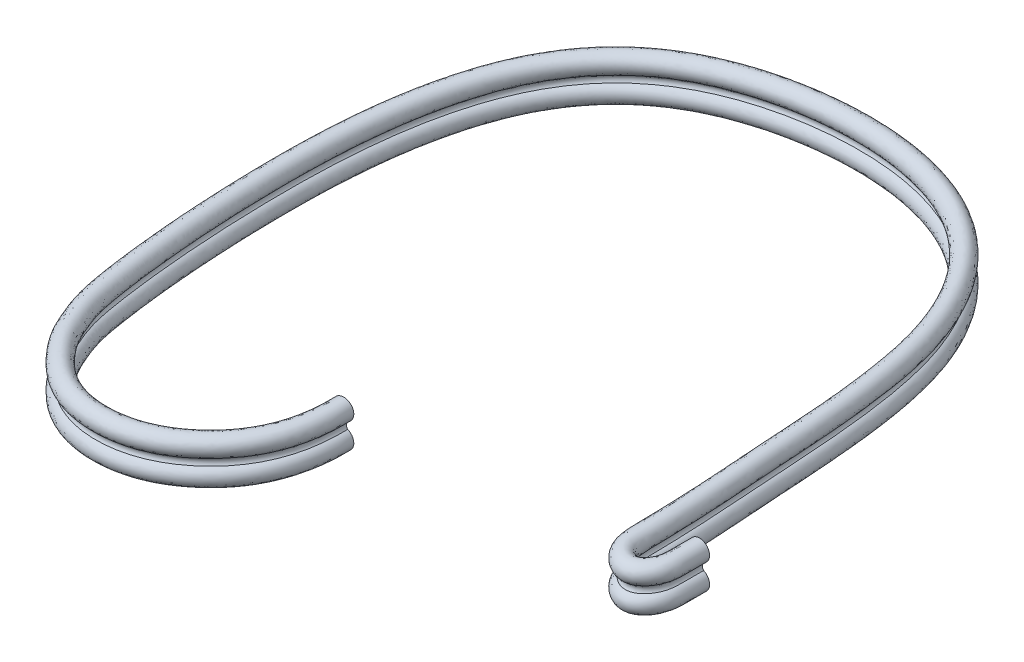
SolidWorks part; units mm, degrees
material "ABS"
ref_plane "Plan de face" through (0, 0, 0) normal (0, 0, 1) x (1, 0, 0)
ref_plane "Plan de dessus" through (0, 0, 0) normal (0, 1, 0) x (1, 0, 0)
ref_plane "Plan de droite" through (0, 0, 0) normal (1, 0, 0) x (0, 0, -1)
sketch "Esquisse1" plane through (0, 0, 0) normal (0, 0, 1) x (1, 0, 0)
  arc A0 (-18.3775, -10.301) -> (-18.0489, -10.301) centre (-18.2132, -10.6657) ccw construction
  arc A1 (-18.3775, -10.301) -> (-18.0489, -10.301) centre (-18.2132, -10.6657) ccw
  arc A2 (-18.0489, -10.0304) -> (-18.0489, -10.301) centre (-17.8955, -10.1657) ccw
  arc A3 (-18.3775, -10.301) -> (-18.3775, -10.0304) centre (-18.5309, -10.1657) ccw construction
  arc A4 (-18.3775, -10.301) -> (-18.3775, -10.0304) centre (-18.5309, -10.1657) ccw
  arc A5 (-18.0489, -10.0304) -> (-18.3775, -10.0304) centre (-18.2132, -9.6657) ccw construction
  arc A6 (-18.0489, -10.0304) -> (-18.3775, -10.0304) centre (-18.2132, -9.6657) ccw
sketch "Esquisse2" plane through (0, -10.1657, 0) normal (0, 1, 0) x (-1, 0, 0)
  line L0 (18.6132, 0) -> (17.8132, 0) construction
  spline S0 degree 3 poles (18.2132, 0) (18.2131, 0.269) (18.213, 0.7207) (18.2139, 1.4918) (18.8445, 2.3266) (19.7802, 1.6372) (19.8062, -1.3841) (20.063, -4.1507) (20.4795, -12.6435) (25.2659, -18.3191) (35.6574, -17.5688) (39.4688, -11.5212) (39.6429, -2.674) (39.0035, 3.1107) (38.6649, 4.1118) (37.8731, 5.8569) (35.689, 7.7295) (31.9405, 7.169) (30.0632, 4.2493) (30.1256, 2.2153) knots 0 0 0 0 0.011019 0.018499 0.028963 0.039203 0.045972 0.095547 0.150587 0.211468 0.306349 0.412438 0.520673 0.638161 0.783375 0.855607 0.914095 0.963999 1 1 1 1
sweep "Balayage4" add profiles "Esquisse1" path "Esquisse2"
